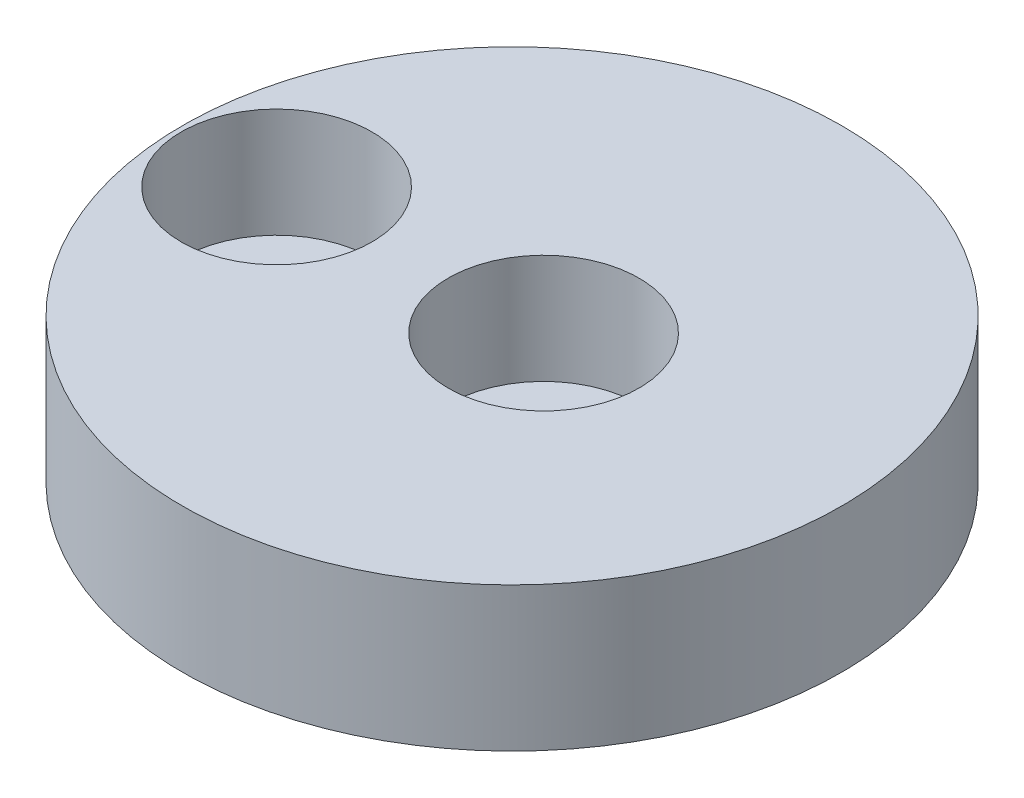
SolidWorks part; units mm, degrees
ref_plane "Płaszczyzna przednia" through (0, 0, 0) normal (0, 0, 1) x (1, 0, 0)
ref_plane "Płaszczyzna górna" through (0, 0, 0) normal (0, 1, 0) x (1, 0, 0)
ref_plane "Płaszczyzna prawa" through (0, 0, 0) normal (1, 0, 0) x (0, 0, -1)
sketch "Szkic1" plane through (0, 0, 0) normal (0, 1, 0) x (1, 0, 0)
  circle A0 centre (0, 0) radius 19
  dimension "D1" = 38
extrude "Dodanie-wyciągnięcie1" add sketch "Szkic1" along normal blind 8.3
sketch "Szkic2" plane through (141.8499, -17.3697, -1004.1033) normal (0, 1, 0) x (0.9997, 0, -0.0265)
  circle A0 centre (-181.5878, -1000) radius 3
  circle A1 centre (-166.5878, -1000) radius 3
  point P6 (-181.5878, -1000)
  dimension "D1" = 15
extrude "Wytnij-wyciągnięcie1" cut sketch "Szkic2" against normal through all both and the other way through all
sketch "Szkic3" plane through (0, 0, 0) normal (0, 1, 0) x (1, 0, 0)
  circle A0 centre (-13.2242, -0.3499) radius 5.5
  circle A1 centre (1.7705, 0.0468) radius 5.5
  dimension "D1" = 11
extrude "Wytnij-wyciągnięcie2" cut sketch "Szkic3" against normal blind 6.3 from surface at 8.3 starting at face at (-13.2242, 8.3, 3.3499)
